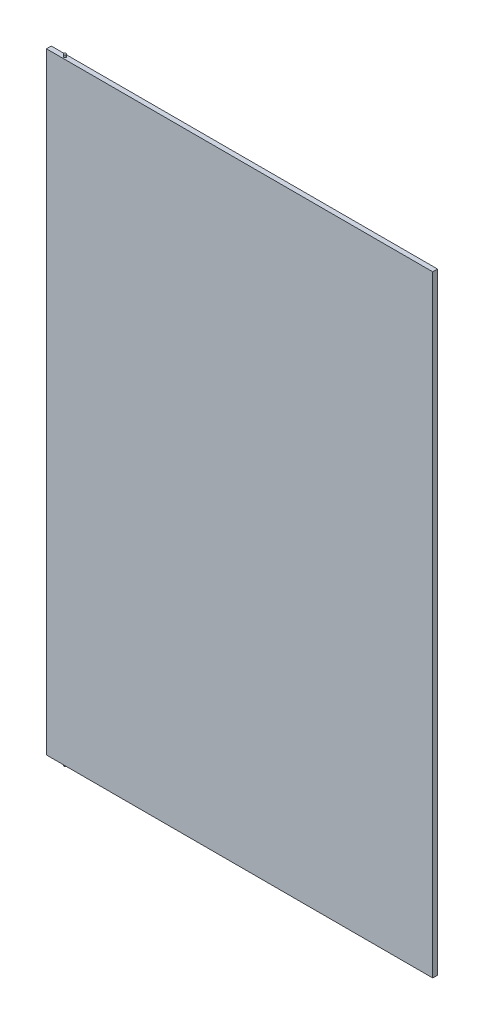
SolidWorks part; units mm, degrees
ref_plane "Alzado" through (0, 0, 0) normal (0, 0, 1) x (1, 0, 0)
ref_plane "Planta" through (0, 0, 0) normal (0, 1, 0) x (1, 0, 0)
ref_plane "Vista lateral" through (0, 0, 0) normal (1, 0, 0) x (0, 0, -1)
sketch "Croquis1" plane through (0, 0, 0) normal (0, 0, 1) x (1, 0, 0)
  line L1 (0, 0) -> (-240, 0)
  line L2 (0, 0) -> (0, 380)
  line L3 (0, 380) -> (-240, 380)
  line L4 (-240, 0) -> (-240, 380)
  dimension "D1" = 240
  dimension "D2" = 380
extrude "Saliente-Extruir1" add sketch "Croquis1" along normal blind 3
sketch "Croquis8" plane through (0, 0, 0) normal (0, -1, 0) x (-1, 0, 0)
  line L0 (240, -3) -> (240, 0) construction
  circle A0 centre (230, -1.4357) radius 0.75
  dimension "D1" = 1.5
  dimension "D2" = 10
extrude "Saliente-Extruir4" add sketch "Croquis8" along normal blind 1.5
sketch "Croquis10" plane through (0, 380, 0) normal (0, 1, 0) x (1, 0, 0)
  line L0 (-240, -1.5) -> (0, -1.5) construction
  line L1 (-240, -3) -> (-240, 0) construction
  line L2 (0, -3) -> (0, 0) construction
  circle A0 centre (-230, -1.5) radius 0.75
  dimension "D1" = 1.5
  dimension "D2" = 10
extrude "Saliente-Extruir5" add sketch "Croquis10" along normal blind 1.5
